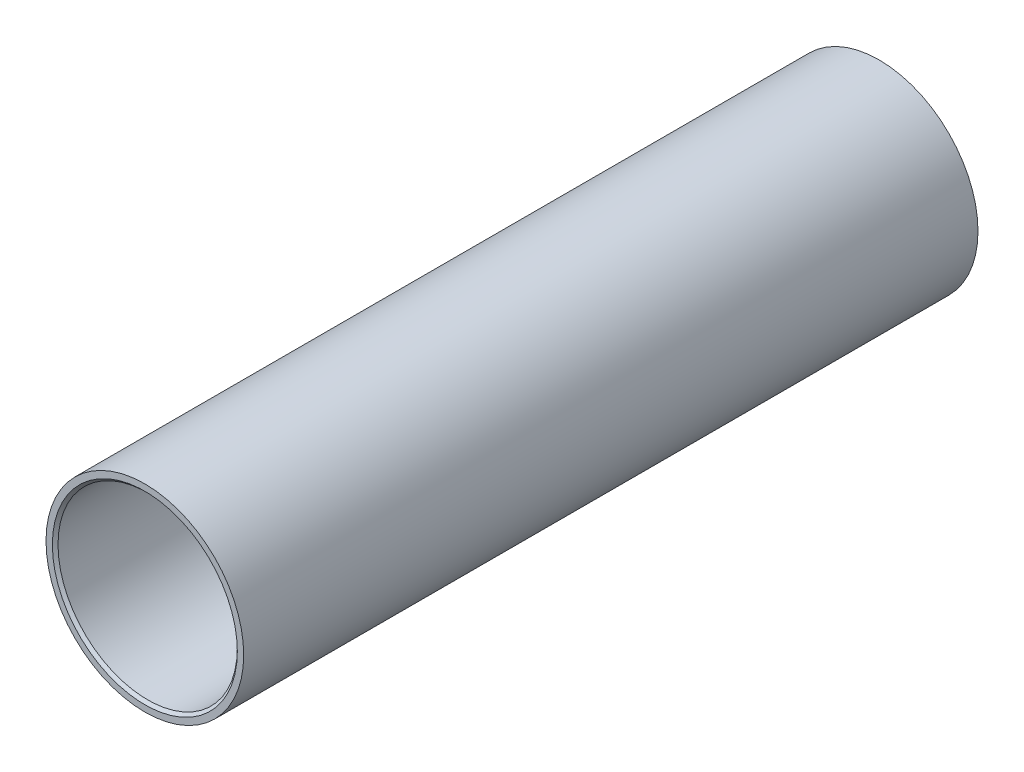
SolidWorks part; units mm, degrees
ref_plane "Ön Düzlem" through (0, 0, 0) normal (0, 0, 1) x (1, 0, 0)
ref_plane "Üst Düzlem" through (0, 0, 0) normal (0, 1, 0) x (1, 0, 0)
ref_plane "Sağ Düzlem" through (0, 0, 0) normal (1, 0, 0) x (0, 0, -1)
sketch "Çizim1" plane through (0, 0, 0) normal (0, 0, 1) x (1, 0, 0)
  circle A0 centre (0, 0) radius 70
  circle A1 centre (0, 0) radius 63.5
  dimension "D1" = 140
  dimension "D2" = 127
extrude "Yükseklik-Ekstrüzyon1" add sketch "Çizim1" along normal blind 520
chamfer "Pah1" distance 2 angle 45 2 edges at (63.5, 0, 0) (63.5, 0, 520)
